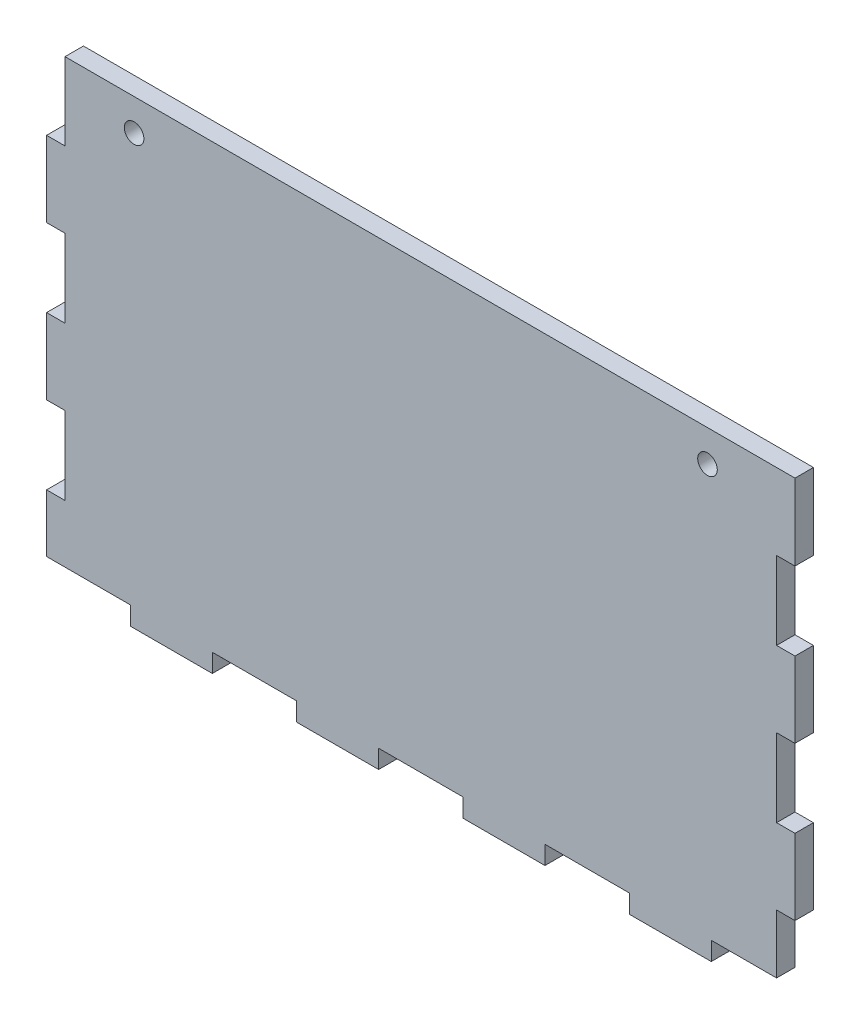
SolidWorks part; units mm, degrees
ref_plane "Front Plane" through (0, 0, 0) normal (0, 0, 1) x (1, 0, 0)
ref_plane "Top Plane" through (0, 0, 0) normal (0, 1, 0) x (1, 0, 0)
ref_plane "Right Plane" through (0, 0, 0) normal (1, 0, 0) x (0, 0, -1)
sketch "Sketch1" plane through (0, 0, 0) normal (0, 0, 1) x (1, 0, 0)
  line L1 (0, 0) -> (130, 0)
  line L2 (0, 0) -> (0, 80)
  line L3 (0, 80) -> (130, 80)
  line L4 (130, 0) -> (130, 80)
  dimension "D1" = 130
  dimension "D2" = 80
extrude "Boss-Extrude1" add sketch "Sketch1" along normal blind 3.2
sketch "Sketch2" plane through (0, 0, 3.2) normal (0, 0, 1) x (1, 0, 0)
  line L61 (14.4444, 3.2) -> (28.8889, 3.2) construction
  line L62 (0, 0) -> (14.4444, 0)
  line L67 (0, 0) -> (0, 3.2)
  line L72 (0, 3.2) -> (14.4444, 3.2)
  line L77 (14.4444, 0) -> (14.4444, 3.2)
  line L97 (28.8889, 0) -> (28.8889, 3.2)
  line L98 (28.8889, 0) -> (43.3333, 0)
  line L107 (43.3333, 0) -> (43.3333, 3.2)
  line L115 (28.8889, 3.2) -> (43.3333, 3.2)
  line L117 (43.3333, 3.2) -> (57.7778, 3.2) construction
  line L123 (57.7778, 0) -> (57.7778, 3.2)
  line L128 (57.7778, 0) -> (72.2222, 0)
  line L129 (72.2222, 0) -> (72.2222, 3.2)
  line L131 (57.7778, 3.2) -> (72.2222, 3.2)
  line L132 (72.2222, 3.2) -> (86.6667, 3.2) construction
  line L133 (86.6667, 0) -> (86.6667, 3.2)
  line L134 (86.6667, 0) -> (101.1111, 0)
  line L135 (101.1111, 0) -> (101.1111, 3.2)
  line L136 (86.6667, 3.2) -> (101.1111, 3.2)
  line L137 (101.1111, 3.2) -> (115.5556, 3.2) construction
  line L138 (115.5556, 0) -> (115.5556, 3.2)
  line L139 (115.5556, 0) -> (130, 0)
  line L142 (130, 0) -> (130, 80) construction
  line L143 (0, 80) -> (0, 0) construction
  line L144 (0, 13.3333) -> (3.2, 13.3333)
  line L145 (0, 13.3333) -> (0, 26.6667)
  line L146 (130, 3.2) -> (144.4444, 3.2) construction
  line L147 (0, 26.6667) -> (3.2, 26.6667)
  line L148 (3.2, 13.3333) -> (3.2, 26.6667)
  line L149 (3.2, 13.3333) -> (3.2, 0) construction
  line L150 (0, 40) -> (0, 53.3333)
  line L151 (0, 40) -> (3.2, 40)
  line L152 (3.2, 40) -> (3.2, 53.3333)
  line L153 (0, 53.3333) -> (3.2, 53.3333)
  line L154 (3.2, 40) -> (3.2, 26.6667) construction
  line L155 (0, 66.6667) -> (0, 80)
  line L156 (0, 66.6667) -> (3.2, 66.6667)
  line L157 (3.2, 66.6667) -> (3.2, 80)
  line L158 (0, 80) -> (3.2, 80)
  line L159 (3.2, 66.6667) -> (3.2, 53.3333) construction
  line L160 (130, 80) -> (0, 80) construction
  line L161 (126.8, 80) -> (126.8, 66.6667) construction
  line L162 (126.8, 40) -> (126.8, 26.6667)
  line L163 (126.8, 66.6667) -> (130, 66.6667)
  line L164 (126.8, 66.6667) -> (126.8, 53.3333)
  line L165 (126.8, 53.3333) -> (130, 53.3333)
  line L166 (130, 66.6667) -> (130, 53.3333)
  line L167 (126.8, 40) -> (130, 40)
  line L168 (130, 40) -> (130, 26.6667)
  line L169 (126.8, 26.6667) -> (130, 26.6667)
  line L170 (126.8, 53.3333) -> (126.8, 40) construction
  line L172 (126.8, 13.3333) -> (130, 13.3333)
  line L173 (130, 13.3333) -> (130, 0)
  line L175 (126.8, 26.6667) -> (126.8, 13.3333) construction
  line L183 (115.5556, 3.2) -> (130, 3.2) [skipped]
  line L184 (130, 0) -> (130, 3.2) [skipped]
  line L185 (126.8, 13.3333) -> (126.8, 3.2)
  line L186 (126.8, 3.2) -> (115.5556, 3.2)
  line L187 (126.8, 0) -> (130, 0) [skipped]
  line L188 (126.8, 13.3333) -> (126.8, 0) [skipped]
  dimension "D2" = 3.2
  dimension "D4" = 3.2
  dimension "D6" = 3.2
  dimension "D1" = 5
  dimension "D3" = 3
  dimension "D5" = 3
extrude "Cut-Extrude1" cut sketch "Sketch2" against normal through all
other "Move Face1" face at (128.4, 53.3333, 1.6) face at (128.4, 26.6667, 1.6) face at (128.4, 13.3333, 1.6) face at (128.4, 40, 1.6) face at (128.4, 66.6667, 1.6) face at (115.5556, 1.6, 1.6) face at (86.6667, 1.6, 1.6) face at (57.7778, 1.6, 1.6) face at (28.8889, 1.6, 1.6) face at (14.4444, 1.6, 1.6) face at (43.3333, 1.6, 1.6) face at (72.2222, 1.6, 1.6) face at (101.1111, 1.6, 1.6) face at (1.6, 26.6667, 1.6) face at (1.6, 13.3333, 1.6) face at (1.6, 40, 1.6) face at (1.6, 53.3333, 1.6) face at (1.6, 66.6667, 1.6) parameters "D1"=0.1
sketch "Sketch3" plane through (0, 0, 3.2) normal (0, 0, 1) x (1, 0, 0)
  line L0 (0, 66.5667) -> (0, 53.4333) construction
  line L1 (130, 80) -> (3.2, 80) construction
  line L2 (0, 66.5667) -> (130, 66.7667) construction
  line L3 (65, 66.6667) -> (65, 50066.6667) construction
  circle A0 centre (15.2, 74.5) radius 1.7
  circle A1 centre (114.8, 74.5) radius 1.7
  point P10 (65, 66.6667)
  dimension "D1" = 3.4
  dimension "D2" = 15.2
  dimension "D3" = 5.5
extrude "Cut-Extrude2" cut sketch "Sketch3" against normal up to next
equation "\"wall_thickness\"= 3.2mm"
equation "\"D1@Boss-Extrude1\"=\"wall_thickness\""
equation "\"slot_width_tolerance\"= 0.1mm"
equation "\"slot_depth\"= 3.2mm"
equation "\"D2@Sketch2\"=\"slot_depth\""
equation "\"D4@Sketch2\"=\"slot_depth\""
equation "\"D6@Sketch2\"=\"slot_depth\""
equation "\"D2@Sketch3\"=12.00mm+\"slot_depth\""
